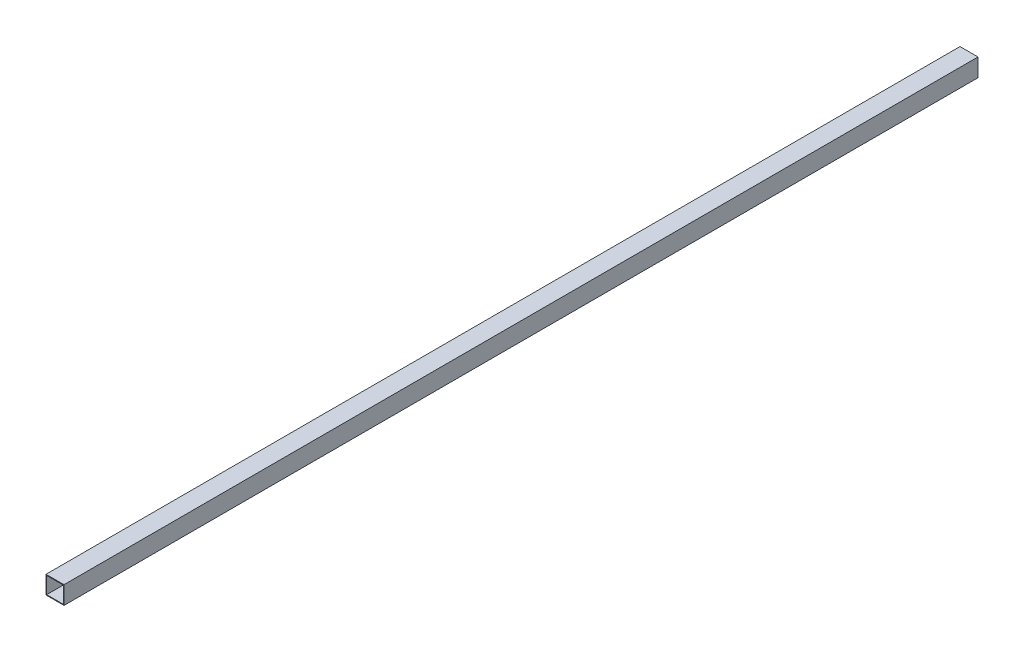
SolidWorks part; units mm, degrees
ref_plane "Front Plane" through (0, 0, 0) normal (0, 0, 1) x (1, 0, 0)
ref_plane "Top Plane" through (0, 0, 0) normal (0, 1, 0) x (1, 0, 0)
ref_plane "Right Plane" through (0, 0, 0) normal (1, 0, 0) x (0, 0, -1)
sketch "Sketch1" plane through (0, 0, 0) normal (0, 0, 1) x (1, 0, 0)
  line L1 (6, 6) -> (-6, 6)
  line L2 (6, 6) -> (6, -6)
  line L3 (6, -6) -> (-6, -6)
  line L4 (-6, 6) -> (-6, -6)
  line L5 (6, 6) -> (-6, -6) construction
  line L6 (6, -6) -> (-6, 6) construction
  line L7 (-6.5, 6.5) -> (6.5, 6.5)
  line L8 (-6.5, 6.5) -> (-6.5, -6.5)
  line L9 (-6.5, -6.5) -> (6.5, -6.5)
  line L10 (6.5, 6.5) -> (6.5, -6.5)
  line L11 (-6.5, 6.5) -> (6.5, -6.5) construction
  line L12 (-6.5, -6.5) -> (6.5, 6.5) construction
  point P1 (0, 0)
  point P6 (0, 0)
  dimension "D1" = 12
  dimension "D2" = 13
  dimension "D3" = 13
  dimension "D4" = 12
extrude "Boss-Extrude1" add sketch "Sketch1" along normal blind 580 and the other way blind 80
